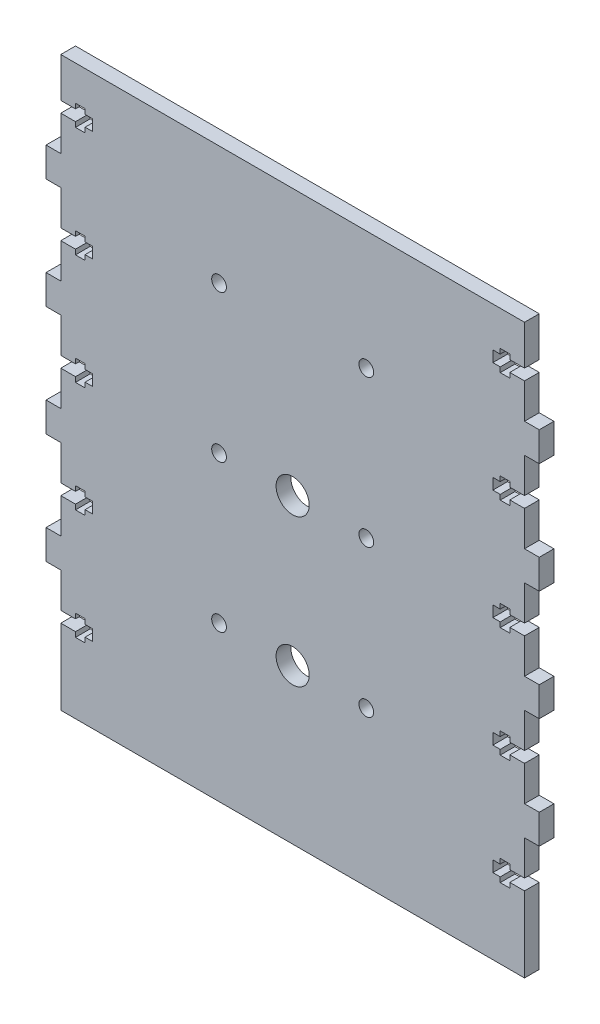
SolidWorks part; units mm, degrees
ref_plane "前视基准面" through (0, 0, 0) normal (0, 0, 1) x (1, 0, 0)
ref_plane "上视基准面" through (0, 0, 0) normal (0, 1, 0) x (1, 0, 0)
ref_plane "右视基准面" through (0, 0, 0) normal (1, 0, 0) x (0, 0, -1)
sketch "草图1" plane through (0, 0, 0) normal (0, 0, 1) x (1, 0, 0)
  line L9 (145, 46.5) -> (149, 46.5)
  line L10 (149, 46.5) -> (149, 45.15)
  line L11 (149, 45.15) -> (151.6, 45.15)
  line L12 (151.6, 45.15) -> (151.6, 46.5)
  line L13 (151.6, 46.5) -> (153.6, 46.5)
  line L14 (153.6, 46.5) -> (153.6, 49.5)
  line L23 (145, 48) -> (143.6922, 48) construction
  line L24 (145, 46.5) -> (145, 49.5) construction
  line L25 (151.6, 50.85) -> (151.6, 49.5)
  line L26 (149, 49.5) -> (149, 50.85)
  line L27 (151.6, 49.5) -> (153.6, 49.5)
  line L28 (149, 50.85) -> (151.6, 50.85)
  line L29 (145, 49.5) -> (149, 49.5)
  line L31 (145, 29) -> (141, 29)
  line L32 (141, 29) -> (141, 37)
  line L33 (141, 37) -> (145, 37)
  line L34 (145, 37) -> (145, 46.5)
  line L35 (141, 33) -> (142.703, 33) construction
  line L43 (149, 15.15) -> (151.6, 15.15)
  line L44 (151.6, 16.5) -> (153.6, 16.5)
  line L45 (149, 16.5) -> (149, 15.15)
  line L69 (262.4, 48) -> (153.6, 48) construction
  line L70 (151.6, 15.15) -> (151.6, 16.5)
  line L71 (153.6, 19.5) -> (153.6, 16.5)
  line L72 (151.6, 19.5) -> (153.6, 19.5)
  line L73 (151.6, 20.85) -> (151.6, 19.5)
  line L98 (149, 20.85) -> (151.6, 20.85)
  line L123 (149, 19.5) -> (149, 20.85)
  line L124 (145, 7) -> (145, 16.5)
  line L125 (149, 16.5) -> (145, 16.5)
  line L126 (149, 19.5) -> (145, 19.5)
  line L127 (145, 19.5) -> (145, 29)
  line L128 (153.6, 18) -> (150.6786, 18) construction
  line L129 (141, 3) -> (142.703, 3) construction
  line L130 (141, -1) -> (145, -1)
  line L131 (141, 7) -> (141, -1)
  line L132 (145, 7) -> (141, 7)
  line L133 (145, -1) -> (145, -10.5)
  line L134 (149, -10.5) -> (145, -10.5)
  line L135 (149, -13.5) -> (145, -13.5)
  line L136 (153.6, -12) -> (150.6786, -12) construction
  line L137 (149, -13.5) -> (149, -14.85)
  line L138 (149, -14.85) -> (151.6, -14.85)
  line L139 (151.6, -14.85) -> (151.6, -13.5)
  line L140 (151.6, -13.5) -> (153.6, -13.5)
  line L141 (153.6, -13.5) -> (153.6, -10.5)
  line L142 (151.6, -9.15) -> (151.6, -10.5)
  line L143 (149, -10.5) -> (149, -9.15)
  line L144 (151.6, -10.5) -> (153.6, -10.5)
  line L145 (149, -9.15) -> (151.6, -9.15)
  line L146 (153.6, 108) -> (150.6786, 108) construction
  line L147 (141, 93) -> (142.703, 93) construction
  line L148 (153.6, 78) -> (150.6786, 78) construction
  line L149 (141, 63) -> (142.703, 63) construction
  line L150 (145, 46.5) -> (149, 46.5)
  line L151 (149, 46.5) -> (149, 45.15)
  line L152 (149, 45.15) -> (151.6, 45.15)
  line L153 (151.6, 45.15) -> (151.6, 46.5)
  line L154 (151.6, 46.5) -> (153.6, 46.5)
  line L155 (151.6, 50.85) -> (151.6, 49.5)
  line L156 (149, 49.5) -> (149, 50.85)
  line L157 (151.6, 49.5) -> (153.6, 49.5)
  line L158 (145, 46.5) -> (149, 46.5)
  line L159 (149, 45.15) -> (151.6, 45.15)
  line L160 (151.6, 46.5) -> (153.6, 46.5)
  line L161 (149, 46.5) -> (149, 45.15)
  line L162 (151.6, 45.15) -> (151.6, 46.5)
  line L163 (151.6, 49.5) -> (153.6, 49.5)
  line L164 (151.6, 50.85) -> (151.6, 49.5)
  line L165 (149, 50.85) -> (151.6, 50.85)
  line L166 (149, 49.5) -> (149, 50.85)
  line L167 (145, 49.5) -> (149, 49.5)
  line L168 (149, 50.85) -> (151.6, 50.85)
  line L169 (145, 49.5) -> (149, 49.5)
  line L170 (149, 105.15) -> (151.6, 105.15)
  line L171 (151.6, 106.5) -> (153.6, 106.5)
  line L172 (149, 106.5) -> (149, 105.15)
  line L173 (151.6, 105.15) -> (151.6, 106.5)
  line L174 (153.6, 109.5) -> (153.6, 106.5)
  line L175 (151.6, 109.5) -> (153.6, 109.5)
  line L177 (151.6, 110.85) -> (151.6, 109.5)
  line L178 (149, 110.85) -> (151.6, 110.85)
  line L179 (149, 109.5) -> (149, 110.85)
  line L180 (149, 109.5) -> (145, 109.5)
  line L181 (149, 106.5) -> (145, 106.5)
  line L182 (145, 97) -> (145, 106.5)
  line L183 (145, 89) -> (141, 89)
  line L184 (141, 89) -> (141, 97)
  line L185 (141, 97) -> (145, 97)
  line L186 (145, 76.5) -> (145, 67)
  line L187 (149, 76.5) -> (145, 76.5)
  line L188 (149, 79.5) -> (145, 79.5)
  line L189 (145, 89) -> (145, 79.5)
  line L190 (149, 76.5) -> (149, 75.15)
  line L191 (149, 75.15) -> (151.6, 75.15)
  line L192 (151.6, 75.15) -> (151.6, 76.5)
  line L193 (151.6, 76.5) -> (153.6, 76.5)
  line L194 (153.6, 76.5) -> (153.6, 79.5)
  line L195 (151.6, 80.85) -> (151.6, 79.5)
  line L196 (149, 79.5) -> (149, 80.85)
  line L197 (151.6, 79.5) -> (153.6, 79.5)
  line L198 (149, 80.85) -> (151.6, 80.85)
  line L199 (145, 59) -> (145, 49.5)
  line L200 (141, 59) -> (145, 59)
  line L201 (141, 67) -> (141, 59)
  line L202 (145, 67) -> (141, 67)
  line L203 (145, 46.5) -> (149, 46.5)
  line L204 (149, 45.15) -> (151.6, 45.15)
  line L205 (151.6, 46.5) -> (153.6, 46.5)
  line L206 (149, 46.5) -> (149, 45.15)
  line L207 (151.6, 45.15) -> (151.6, 46.5)
  line L208 (151.6, 49.5) -> (153.6, 49.5)
  line L209 (151.6, 50.85) -> (151.6, 49.5)
  line L210 (149, 50.85) -> (151.6, 50.85)
  line L211 (149, 49.5) -> (149, 50.85)
  line L212 (145, 49.5) -> (149, 49.5)
  line L213 (275, 63) -> (273.297, 63) construction
  line L214 (262.4, 78) -> (265.3214, 78) construction
  line L215 (275, 93) -> (273.297, 93) construction
  line L216 (262.4, 108) -> (265.3214, 108) construction
  line L217 (262.4, -12) -> (265.3214, -12) construction
  line L218 (275, 3) -> (273.297, 3) construction
  line L219 (262.4, 18) -> (265.3214, 18) construction
  line L220 (275, 33) -> (273.297, 33) construction
  line L221 (271, 46.5) -> (271, 49.5) construction
  line L222 (271, 48) -> (272.3078, 48) construction
  line L223 (271, -27) -> (271, -13.5)
  line L224 (271, 123) -> (271, 109.5)
  line L225 (271, -27) -> (271, -34)
  line L227 (271, 49.5) -> (267, 49.5)
  line L228 (267, 49.5) -> (267, 50.85)
  line L229 (267, 50.85) -> (264.4, 50.85)
  line L230 (264.4, 50.85) -> (264.4, 49.5)
  line L231 (264.4, 49.5) -> (262.4, 49.5)
  line L232 (264.4, 45.15) -> (264.4, 46.5)
  line L233 (267, 46.5) -> (267, 45.15)
  line L234 (264.4, 46.5) -> (262.4, 46.5)
  line L235 (267, 45.15) -> (264.4, 45.15)
  line L253 (271, 46.5) -> (267, 46.5)
  line L254 (271, 67) -> (275, 67)
  line L255 (145, -27) -> (145, -34)
  line L256 (208, 48) -> (208, 8) construction
  line L257 (208, 8) -> (188, 8) construction
  line L258 (275, 67) -> (275, 59)
  line L259 (275, 59) -> (271, 59)
  line L260 (271, 59) -> (271, 49.5)
  line L261 (267, 80.85) -> (264.4, 80.85)
  line L262 (264.4, 79.5) -> (262.4, 79.5)
  line L263 (267, 79.5) -> (267, 80.85)
  line L264 (264.4, 80.85) -> (264.4, 79.5)
  line L265 (262.4, 76.5) -> (262.4, 79.5)
  line L267 (264.4, 76.5) -> (262.4, 76.5)
  line L269 (264.4, 75.15) -> (264.4, 76.5)
  line L270 (267, 75.15) -> (264.4, 75.15)
  line L272 (267, 76.5) -> (267, 75.15)
  line L273 (271, 89) -> (271, 79.5)
  line L274 (267, 79.5) -> (271, 79.5)
  line L275 (267, 76.5) -> (271, 76.5)
  line L277 (271, 76.5) -> (271, 67)
  line L278 (275, 97) -> (271, 97)
  line L279 (275, 89) -> (275, 97)
  line L280 (271, 89) -> (275, 89)
  line L281 (271, 97) -> (271, 106.5)
  line L282 (267, 106.5) -> (271, 106.5)
  line L283 (267, 109.5) -> (271, 109.5)
  line L284 (267, 109.5) -> (267, 110.85)
  line L285 (267, 110.85) -> (264.4, 110.85)
  line L286 (264.4, 110.85) -> (264.4, 109.5)
  line L287 (264.4, 109.5) -> (262.4, 109.5)
  line L288 (262.4, 109.5) -> (262.4, 106.5)
  line L289 (264.4, 105.15) -> (264.4, 106.5)
  line L290 (267, 106.5) -> (267, 105.15)
  line L291 (264.4, 106.5) -> (262.4, 106.5)
  line L292 (267, 105.15) -> (264.4, 105.15)
  line L293 (271, 49.5) -> (267, 49.5)
  line L294 (267, 50.85) -> (264.4, 50.85)
  line L295 (271, 49.5) -> (267, 49.5)
  line L296 (267, 49.5) -> (267, 50.85)
  line L298 (267, 50.85) -> (264.4, 50.85)
  line L299 (264.4, 50.85) -> (264.4, 49.5)
  line L300 (264.4, 49.5) -> (262.4, 49.5)
  line L301 (264.4, 45.15) -> (264.4, 46.5)
  line L302 (267, 46.5) -> (267, 45.15)
  line L303 (264.4, 46.5) -> (262.4, 46.5)
  line L304 (267, 45.15) -> (264.4, 45.15)
  line L305 (271, 46.5) -> (267, 46.5)
  line L306 (264.4, 49.5) -> (262.4, 49.5)
  line L307 (267, 49.5) -> (267, 50.85)
  line L308 (264.4, 50.85) -> (264.4, 49.5)
  line L309 (264.4, 46.5) -> (262.4, 46.5)
  line L310 (264.4, 45.15) -> (264.4, 46.5)
  line L312 (267, 45.15) -> (264.4, 45.15)
  line L314 (267, 46.5) -> (267, 45.15)
  line L315 (271, 46.5) -> (267, 46.5)
  line L317 (267, -9.15) -> (264.4, -9.15)
  line L320 (264.4, -10.5) -> (262.4, -10.5)
  line L321 (267, -10.5) -> (267, -9.15)
  line L322 (264.4, -9.15) -> (264.4, -10.5)
  line L323 (262.4, -13.5) -> (262.4, -10.5)
  line L324 (264.4, -13.5) -> (262.4, -13.5)
  line L325 (264.4, -14.85) -> (264.4, -13.5)
  line L326 (267, -14.85) -> (264.4, -14.85)
  line L327 (267, -13.5) -> (267, -14.85)
  line L328 (267, -13.5) -> (271, -13.5)
  line L329 (267, -10.5) -> (271, -10.5)
  line L330 (271, -1) -> (271, -10.5)
  line L331 (271, 7) -> (275, 7)
  line L332 (275, 7) -> (275, -1)
  line L333 (275, -1) -> (271, -1)
  line L334 (271, 19.5) -> (271, 29)
  line L335 (267, 19.5) -> (271, 19.5)
  line L336 (267, 16.5) -> (271, 16.5)
  line L337 (271, 7) -> (271, 16.5)
  line L338 (267, 19.5) -> (267, 20.85)
  line L339 (267, 20.85) -> (264.4, 20.85)
  line L340 (264.4, 20.85) -> (264.4, 19.5)
  line L341 (264.4, 19.5) -> (262.4, 19.5)
  line L342 (262.4, 19.5) -> (262.4, 16.5)
  line L343 (264.4, 15.15) -> (264.4, 16.5)
  line L344 (267, 16.5) -> (267, 15.15)
  line L345 (264.4, 16.5) -> (262.4, 16.5)
  line L346 (267, 15.15) -> (264.4, 15.15)
  line L347 (271, 37) -> (271, 46.5)
  line L348 (275, 37) -> (271, 37)
  line L349 (275, 29) -> (275, 37)
  line L350 (271, 29) -> (275, 29)
  line L351 (271, 49.5) -> (267, 49.5)
  line L352 (267, 50.85) -> (264.4, 50.85)
  line L353 (264.4, 49.5) -> (262.4, 49.5)
  line L354 (267, 49.5) -> (267, 50.85)
  line L355 (264.4, 50.85) -> (264.4, 49.5)
  line L356 (262.4, 46.5) -> (262.4, 49.5)
  line L357 (264.4, 46.5) -> (262.4, 46.5)
  line L358 (264.4, 45.15) -> (264.4, 46.5)
  line L359 (267, 45.15) -> (264.4, 45.15)
  line L360 (267, 46.5) -> (267, 45.15)
  line L361 (271, 46.5) -> (267, 46.5)
  line L362 (145, 123) -> (271, 123)
  line L363 (145, -34) -> (271, -34)
  line L592 (145, 123) -> (145, 109.5)
  line L594 (145, -27) -> (145, -13.5)
  circle A69 centre (188, 8) radius 2
  circle A70 centre (228, 8) radius 2
  circle A71 centre (228, 88) radius 2
  circle A72 centre (188, 88) radius 2
  point P15 (144.3461, 48)
  dimension "D2" = 40
  dimension "D1" = 15
  dimension "D9" = 63
  dimension "D3" = 4
  dimension "D4" = 2
  dimension "D5" = 2.6
  dimension "D6" = 1.35
  dimension "D8" = 1.5
  dimension "D10" = 40
extrude "凸台-拉伸1" add sketch "草图1" along normal blind 4 contours L594 L255 L363 L225 L223 L328 L327 L326 L325 L324 L323 L320 L322 L317 L321 L329 L330 L333 L332 L331 L337 L336 L344 L346 L343 L345 L342 L341 L340 L339 L338 L335 L334 L350 L349 L348 L347 L253 L233 L235 L232 L234 L356 L231 L230 L229 L228 L227 L260 L259 L258
sketch "草图2" plane through (271, 0, 0) normal (1, 0, 0) x (0, 0, -1)
  line L0 (-2, -10.5) -> (-2, -13.5)
  line L1 (-4, -10.5) -> (0, -10.5) construction
  line L2 (-4, -13.5) -> (0, -13.5) construction
  circle A0 centre (-2, -12) radius 1.5
sketch "草图3" plane through (0, 0, 4) normal (0, 0, 1) x (1, 0, 0)
  line L0 (271, 123) -> (271, 109.5) construction
  line L1 (145, 123) -> (271, 123)
  line L2 (145, 123) -> (145, 120.3)
  line L3 (145, 120.3) -> (271, 120.3)
  line L4 (271, 123) -> (271, 120.3)
  dimension "D1" = 2.7
extrude "切除-拉伸1" cut sketch "草图3" against normal blind 10
sketch "草图4" plane through (0, 0, 4) normal (0, 0, 1) x (1, 0, 0)
  line L0 (188, 8) -> (228, 8) construction
  line L1 (208, 8) -> (208, 48) construction
  circle A0 centre (208, 8) radius 4.5
  circle A1 centre (228, 48) radius 2
  circle A2 centre (188, 48) radius 2
  circle A3 centre (208, 48) radius 4.5
extrude "切除-拉伸2" cut sketch "草图4" against normal blind 10
